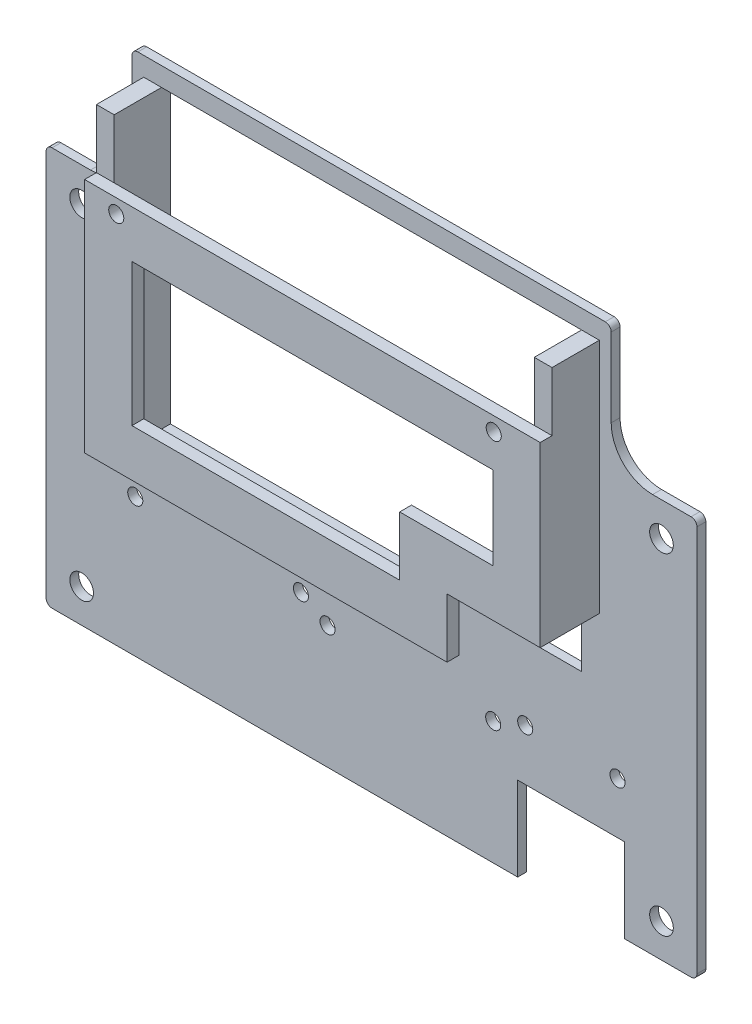
SolidWorks part; units mm, degrees
ref_plane "前基準面" through (0, 0, 0) normal (0, 0, 1) x (1, 0, 0)
ref_plane "上基準面" through (0, 0, 0) normal (0, 1, 0) x (1, 0, 0)
ref_plane "右基準面" through (0, 0, 0) normal (1, 0, 0) x (0, 0, -1)
sketch "草圖1" plane through (0, 0, 0) normal (0, 0, 1) x (1, 0, 0)
  line L5 (-78.5836, -93.3419) -> (16.5192, -93.3419)
  line L36 (9.5192, -18.9462) -> (9.5192, -5.6591)
  line L37 (8.5192, -4.6591) -> (-70.4808, -4.6591)
  line L38 (-71.4808, -5.6591) -> (-71.4808, -18.9462)
  line L39 (-78.4808, -25.9462) -> (-84.9808, -25.9462)
  line L40 (-85.9808, -26.9462) -> (-85.9808, -92.3419)
  line L41 (-84.9834, -93.3419) -> (-78.5836, -93.3419)
  line L45 (16.5192, -93.3419) -> (23.0192, -93.3419)
  line L46 (24.0192, -92.3419) -> (24.0192, -26.9161)
  line L47 (23.0192, -25.9462) -> (16.5192, -25.9462)
  circle A12 centre (-79.9808, -31.644) radius 2
  circle A13 centre (18.0192, -31.644) radius 2
  circle A14 centre (18.0192, -87.644) radius 2
  circle A15 centre (-79.9808, -87.644) radius 2
  arc A36 (9.5192, -18.9462) -> (16.5192, -25.9462) centre (16.5192, -18.9462) ccw
  arc A37 (9.5192, -5.6591) -> (8.5192, -4.6591) centre (8.5192, -5.6591) ccw
  arc A38 (-70.4808, -4.6591) -> (-71.4808, -5.6591) centre (-70.4808, -5.6591) ccw
  arc A39 (-78.4808, -25.9462) -> (-71.4808, -18.9462) centre (-78.4808, -18.9462) ccw
  arc A40 (-84.9808, -25.9462) -> (-85.9808, -26.9462) centre (-84.9808, -26.9462) ccw
  arc A41 (-85.9808, -92.3419) -> (-84.9834, -93.3419) centre (-84.9808, -92.3419) ccw
  arc A46 (23.0192, -93.3419) -> (24.0192, -92.3419) centre (23.0192, -92.3419) ccw
  arc A47 (24.0192, -26.9161) -> (23.0192, -25.9462) centre (23.0196, -26.9462) ccw
  dimension "D2" = 4
  dimension "D3" = 4
  dimension "D4" = 4
  dimension "D5" = 4
extrude "填料-伸長1" add sketch "草圖1" along normal blind 1.5
sketch "草圖2" plane through (0, 0, 1.5) normal (0, 0, 1) x (1, 0, 0)
  line L0 (-71.4808, -5.6591) -> (-71.4808, -18.9462) construction
  line L1 (-69.4808, -7.8571) -> (-66.4808, -7.8571)
  line L2 (-69.4808, -7.8571) -> (-69.4808, -57.8571)
  line L3 (-69.4808, -57.8571) -> (-66.4808, -57.8571)
  line L4 (-66.4808, -7.8571) -> (-66.4808, -57.8571)
  line L5 (4.5192, -7.8571) -> (7.5192, -7.8571)
  line L6 (4.5192, -7.8571) -> (4.5192, -47.8571)
  line L7 (4.5192, -47.8571) -> (7.5192, -47.8571)
  line L8 (7.5192, -7.8571) -> (7.5192, -47.8571)
  line L9 (9.5192, -18.9462) -> (9.5192, -5.6591) construction
  dimension "D1" = 3
  dimension "D2" = 50
  dimension "D3" = 2
  dimension "D4" = 2
  dimension "D5" = 3
  dimension "D6" = 40
extrude "填料-伸長3" add sketch "草圖2" along normal blind 8
sketch "草圖3" plane through (0, 0, 9.5) normal (0, 0, 1) x (1, 0, 0)
  line L0 (-69.4808, -57.8571) -> (-66.4808, -57.8571) construction
  line L1 (-69.4808, -17.828) -> (7.5192, -17.828)
  line L2 (-69.4808, -17.828) -> (-69.4808, -57.8571)
  line L3 (-69.4808, -57.8571) -> (-8.2251, -57.8571)
  line L4 (7.5192, -17.828) -> (7.5192, -47.8571)
  line L6 (7.5192, -47.8571) -> (-8.2251, -47.8571)
  line L9 (-8.2251, -47.8571) -> (-8.2251, -57.8571)
extrude "填料-伸長4" add sketch "草圖3" along normal blind 2
sketch "草圖4" plane through (0, 0, 1.5) normal (0, 0, 1) x (1, 0, 0)
  line L1 (-66.4808, -57.8571) -> (4.5192, -57.8571)
  line L2 (-66.4808, -57.8571) -> (-66.4808, -7.8571)
  line L3 (-66.4808, -7.8571) -> (4.5192, -7.8571)
  line L4 (4.5192, -57.8571) -> (4.5192, -7.8571)
extrude "除料-伸長1" cut sketch "草圖4" against normal through all
sketch "草圖7" plane through (0, 0, 11.5) normal (0, 0, 1) x (1, 0, 0)
  line L6 (-16.2251, -49.8571) -> (-16.2251, -39.8571)
  line L7 (-16.2251, -49.8571) -> (-16.2251, -39.8571)
  line L8 (-61.4808, -25.828) -> (-61.4808, -49.8571)
  line L9 (-61.4808, -49.8571) -> (-16.2251, -49.8571)
  line L10 (-0.4808, -39.8571) -> (-0.4808, -25.828)
  line L11 (-0.4808, -25.828) -> (-61.4808, -25.828)
  line L12 (-61.4808, -25.828) -> (-61.4808, -49.8571)
  line L13 (-61.4808, -49.8571) -> (-16.2251, -49.8571)
  line L14 (-0.4808, -39.8571) -> (-0.4808, -25.828)
  line L15 (-0.4808, -25.828) -> (-61.4808, -25.828)
  line L16 (-16.2251, -39.8571) -> (-0.4808, -39.8571)
  line L17 (-16.2251, -39.8571) -> (-0.4808, -39.8571)
  dimension "D1" = 8
extrude "除料-伸長3" cut sketch "草圖7" against normal through all
sketch "草圖11" plane through (0, 0, 1.5) normal (0, 0, 1) x (1, 0, 0)
  line L0 (-84.9834, -93.3419) -> (23.0192, -93.3419) construction
  line L1 (11.7894, -79.1442) -> (-6.2856, -79.1442)
  line L2 (11.7894, -79.1442) -> (11.7894, -93.3419)
  line L3 (11.7894, -93.3419) -> (-6.2856, -93.3419)
  line L4 (-6.2856, -79.1442) -> (-6.2856, -93.3419)
extrude "除料-伸長4" cut sketch "草圖11" against normal through all
hole_wizard "M2.5 螺旋的螺孔鑽1" positions "草圖12" profile "草圖13" hole size "M2.5x0.45" standard "Ansi Metric" end condition through all
sketch "草圖12" plane through (0, 0, 0) normal (0, 0, 1) x (1, 0, 0)
  point P0 (-64.1308, -20.2071)
  point P2 (-0.3308, -20.2071)
  point P4 (10.5894, -70.472)
  point P6 (-5.0106, -70.472)
  point P8 (-10.4197, -72.5712)
  point P10 (-38.4197, -72.5712)
  point P12 (-42.9197, -69.9617)
  point P14 (-70.9197, -69.9617)
sketch "草圖13" plane through (-64.1308, -20.2071, 0) normal (1, 0, 0) x (0, 1, 0)
  line L0 (0, 0) -> (0, 11.5)
  line L1 (0, 11.5) -> (1.275, 11.5)
  line L2 (1.275, 11.5) -> (1.275, 0)
  line L5 (1.275, 0) -> (0, 0)
  line L11 (0, -6.35) -> (0, 107.95) construction
  dimension "貫穿孔直徑" = 2.55
  dimension "貫穿孔深度" = 11.5
